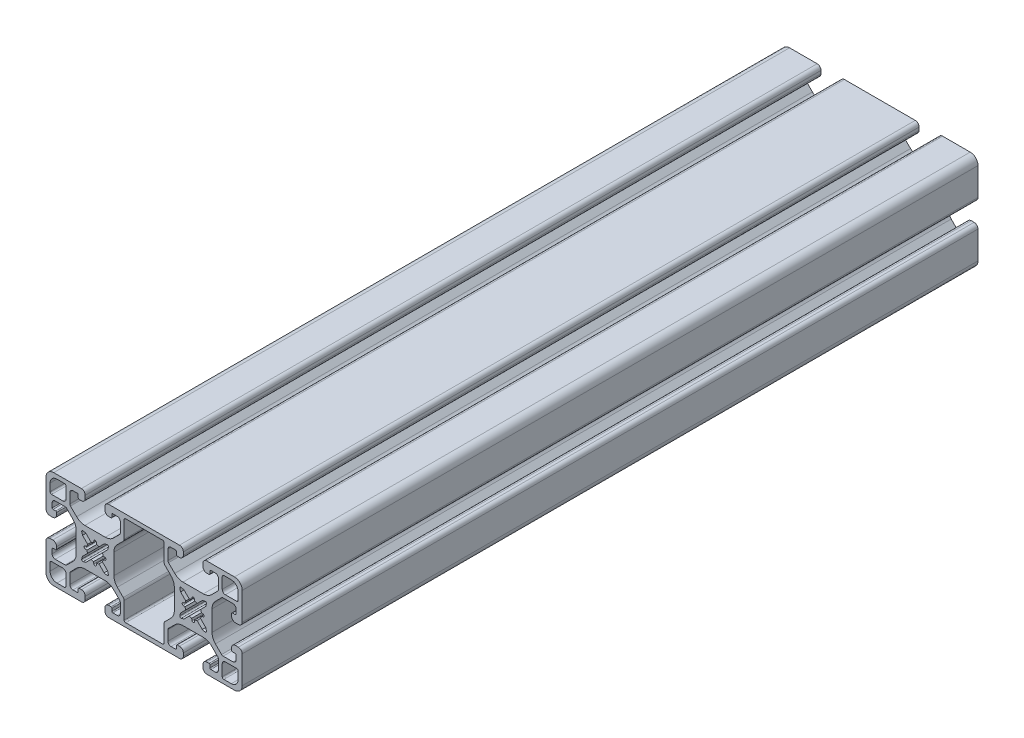
SolidWorks part; units mm, degrees
material "6105-T5 Aluminum"
ref_plane "Front Plane" through (0, 0, 0) normal (0, 0, 1) x (1, 0, 0)
ref_plane "Top Plane" through (0, 0, 0) normal (0, 1, 0) x (1, 0, 0)
ref_plane "Right Plane" through (0, 0, 0) normal (1, 0, 0) x (0, 0, -1)
sketch "Sketch1" plane through (0, 0, 0) normal (0, 0, 1) x (1, 0, 0)
  line L0 (-44, -18.4848) -> (-44, -17.255)
  line L1 (-46.474, -15.685) -> (-45.57, -15.685)
  line L2 (-56.83, -20) -> (-45.569, -20)
  line L3 (-46.855, -17.119) -> (-46.855, -16.066)
  line L4 (-60, -16.83) -> (-60, -5.57)
  line L5 (-49.015, -17.5) -> (-47.236, -17.5)
  line L6 (-58.43, -4) -> (-57.255, -4)
  line L7 (-50.285, -16.23) -> (-50.285, -12.2162)
  line L8 (-55.685, -5.57) -> (-55.685, -6.474)
  line L9 (-47.5137, -9.0762) -> (-50.0243, -11.5869)
  line L10 (-57.119, -6.855) -> (-56.066, -6.855)
  line L11 (-44.1549, -7.685) -> (-35.8451, -7.685)
  line L12 (-57.5, -9.015) -> (-57.5, -7.236)
  line L13 (-32.4863, -9.0762) -> (-29.9757, -11.5869)
  line L14 (-56.23, -10.285) -> (-52.2162, -10.285)
  line L15 (-29.715, -16.23) -> (-29.715, -12.2162)
  line L16 (-49.0762, -7.5137) -> (-51.5869, -10.0243)
  line L17 (-30.985, -17.5) -> (-32.764, -17.5)
  line L18 (-47.685, 4.1549) -> (-47.685, -4.1549)
  line L19 (-33.145, -17.119) -> (-33.145, -16.066)
  line L20 (-49.0762, 7.5137) -> (-51.5869, 10.0243)
  line L21 (-34.43, -15.685) -> (-33.526, -15.685)
  line L22 (-56.23, 10.285) -> (-52.2162, 10.285)
  line L23 (-36, -18.4848) -> (-36, -17.255)
  line L24 (-57.5, 9.015) -> (-57.5, 7.236)
  line L25 (-5.57, -20) -> (-34.431, -20)
  line L26 (-57.119, 6.855) -> (-56.066, 6.855)
  line L27 (-4, -17.255) -> (-4, -18.43)
  line L28 (-55.685, 6.474) -> (-55.685, 5.57)
  line L29 (-5.57, -15.685) -> (-6.474, -15.685)
  line L30 (-58.43, 4) -> (-57.255, 4)
  line L31 (-6.855, -17.119) -> (-6.855, -16.066)
  line L32 (-60, 16.83) -> (-60, 5.57)
  line L33 (-9.015, -17.5) -> (-7.236, -17.5)
  line L34 (-56.83, 20) -> (-45.57, 20)
  line L35 (-10.285, -16.23) -> (-10.285, -12.2162)
  line L36 (-44, 18.43) -> (-44, 17.255)
  line L37 (-7.5137, -9.0762) -> (-10.0243, -11.5869)
  line L38 (-45.57, 15.685) -> (-46.474, 15.685)
  line L39 (4.1549, -7.685) -> (-4.1549, -7.685)
  line L40 (-46.855, 17.119) -> (-46.855, 16.066)
  line L41 (7.5137, -9.0762) -> (10.0243, -11.5869)
  line L42 (-49.015, 17.5) -> (-47.236, 17.5)
  line L43 (10.285, -16.23) -> (10.285, -12.2162)
  line L44 (-50.285, 16.23) -> (-50.285, 12.2162)
  line L45 (9.015, -17.5) -> (7.236, -17.5)
  line L46 (-47.5137, 9.0762) -> (-50.0243, 11.5869)
  line L47 (6.855, -17.119) -> (6.855, -16.066)
  line L48 (-35.8451, 7.685) -> (-44.1549, 7.685)
  line L49 (6.474, -15.685) -> (5.57, -15.685)
  line L50 (-32.4863, 9.0762) -> (-29.9757, 11.5869)
  line L51 (4, -17.255) -> (4, -18.43)
  line L52 (-29.715, 16.23) -> (-29.715, 12.2162)
  line L53 (16.83, -20) -> (5.57, -20)
  line L54 (-30.985, 17.5) -> (-32.764, 17.5)
  line L55 (20, -16.83) -> (20, -5.57)
  line L56 (-33.145, 17.119) -> (-33.145, 16.066)
  line L57 (17.255, -4) -> (18.43, -4)
  line L58 (-33.526, 15.685) -> (-34.43, 15.685)
  line L59 (15.685, -5.57) -> (15.685, -6.474)
  line L60 (-36, 18.43) -> (-36, 17.255)
  line L61 (17.119, -6.855) -> (16.066, -6.855)
  line L62 (-34.43, 20) -> (-5.57, 20)
  line L63 (17.5, -9.015) -> (17.5, -7.236)
  line L64 (-4, 18.43) -> (-4, 17.255)
  line L65 (16.23, -10.285) -> (12.2162, -10.285)
  line L66 (-6.474, 15.685) -> (-5.57, 15.685)
  line L67 (9.0762, -7.5137) -> (11.5869, -10.0243)
  line L68 (-6.855, 17.119) -> (-6.855, 16.066)
  line L69 (7.685, 4.1549) -> (7.685, -4.1549)
  line L70 (-9.015, 17.5) -> (-7.236, 17.5)
  line L71 (9.0762, 7.5137) -> (11.5869, 10.0243)
  line L72 (-10.285, 16.23) -> (-10.285, 12.2162)
  line L73 (16.23, 10.285) -> (12.2162, 10.285)
  line L74 (-7.5137, 9.0762) -> (-10.0243, 11.5869)
  line L75 (17.5, 9.015) -> (17.5, 7.236)
  line L76 (-4.1549, 7.685) -> (4.1549, 7.685)
  line L77 (17.119, 6.855) -> (16.066, 6.855)
  line L78 (7.5137, 9.0762) -> (10.0243, 11.5869)
  line L79 (15.685, 6.474) -> (15.685, 5.57)
  line L80 (10.285, 16.23) -> (10.285, 12.2162)
  line L81 (17.255, 4) -> (18.43, 4)
  line L82 (9.015, 17.5) -> (7.236, 17.5)
  line L83 (20, 16.83) -> (20, 5.57)
  line L84 (6.855, 17.119) -> (6.855, 16.066)
  line L85 (16.83, 20) -> (5.57, 20)
  line L86 (5.57, 15.685) -> (6.474, 15.685)
  line L87 (4, 18.43) -> (4, 17.255)
  line L88 (15.545, -18.345) -> (12.4898, -18.345)
  line L89 (18.345, -12.4898) -> (18.345, -15.545)
  line L90 (11.8598, -17.715) -> (11.8598, -13.1298)
  line L91 (13.1298, -11.8598) -> (17.715, -11.8598)
  line L92 (-11.8598, 17.715) -> (-11.8598, 10.8233)
  line L93 (-11.4878, 9.9253) -> (-9.0762, 7.5137)
  line L94 (-27.5102, 18.345) -> (-12.4898, 18.345)
  line L95 (-7.685, 4.1549) -> (-7.685, -4.1549)
  line L96 (-28.1402, 10.8233) -> (-28.1402, 17.715)
  line L97 (-9.0762, -7.5137) -> (-11.4878, -9.9253)
  line L98 (-30.9238, 7.5137) -> (-28.5122, 9.9253)
  line L99 (-11.8598, -10.8233) -> (-11.8598, -17.715)
  line L100 (-32.315, -4.1549) -> (-32.315, 4.1549)
  line L101 (-12.4898, -18.345) -> (-27.5102, -18.345)
  line L102 (-28.5122, -9.9253) -> (-30.9238, -7.5137)
  line L103 (-28.1402, -17.715) -> (-28.1402, -10.8233)
  line L104 (-58.345, -15.545) -> (-58.345, -12.4898)
  line L105 (-52.4898, -18.345) -> (-55.545, -18.345)
  line L106 (-57.715, -11.8598) -> (-53.1298, -11.8598)
  line L107 (-51.8598, -13.1298) -> (-51.8598, -17.715)
  line L108 (-55.545, 18.345) -> (-52.4898, 18.345)
  line L109 (-58.345, 12.4898) -> (-58.345, 15.545)
  line L110 (-51.8598, 17.715) -> (-51.8598, 13.1298)
  line L111 (-53.1298, 11.8598) -> (-57.715, 11.8598)
  line L112 (18.345, 15.545) -> (18.345, 12.4898)
  line L113 (12.4898, 18.345) -> (15.545, 18.345)
  line L114 (17.715, 11.8598) -> (13.1298, 11.8598)
  line L115 (11.8598, 13.1298) -> (11.8598, 17.715)
  line L116 (-34.8737, -3.712) -> (-34.5607, -4.8481)
  line L117 (-36.9951, -1.5907) -> (-34.8737, -3.712)
  line L118 (-35.1519, -5.4393) -> (-36.288, -5.1263)
  line L119 (-36.288, -5.1263) -> (-38.4093, -3.0049)
  line L120 (-35.9124, -0.4923) -> (-36.6579, -0.625)
  line L121 (-39.375, -3.3421) -> (-39.5077, -4.0876)
  line L122 (-36.6579, 0.625) -> (-35.9124, 0.4923)
  line L123 (-40.4923, -4.0876) -> (-40.625, -3.3421)
  line L124 (-34.8737, 3.712) -> (-36.9951, 1.5907)
  line L125 (-34.5607, 4.8481) -> (-34.8737, 3.712)
  line L126 (-41.5907, -3.0049) -> (-43.712, -5.1263)
  line L127 (-43.712, -5.1263) -> (-44.8481, -5.4393)
  line L128 (-36.288, 5.1263) -> (-35.1519, 5.4393)
  line L129 (-38.4093, 3.0049) -> (-36.288, 5.1263)
  line L130 (-45.4393, -4.8481) -> (-45.1263, -3.712)
  line L131 (-45.1263, -3.712) -> (-43.0049, -1.5907)
  line L132 (-39.5077, 4.0876) -> (-39.375, 3.3421)
  line L133 (-43.3421, -0.625) -> (-44.0876, -0.4923)
  line L134 (-40.625, 3.3421) -> (-40.4923, 4.0876)
  line L135 (-44.0876, 0.4923) -> (-43.3421, 0.625)
  line L136 (-43.712, 5.1263) -> (-41.5907, 3.0049)
  line L137 (-44.8481, 5.4393) -> (-43.712, 5.1263)
  line L138 (-43.0049, 1.5907) -> (-45.1263, 3.712)
  line L139 (-45.1263, 3.712) -> (-45.4393, 4.8481)
  line L140 (5.1263, -3.712) -> (5.4393, -4.8481)
  line L141 (3.0049, -1.5907) -> (5.1263, -3.712)
  line L142 (4.8481, -5.4393) -> (3.712, -5.1263)
  line L143 (3.712, -5.1263) -> (1.5907, -3.0049)
  line L144 (4.0876, -0.4923) -> (3.3421, -0.625)
  line L145 (0.625, -3.3421) -> (0.4923, -4.0876)
  line L146 (3.3421, 0.625) -> (4.0876, 0.4923)
  line L147 (-0.4923, -4.0876) -> (-0.625, -3.3421)
  line L148 (5.1263, 3.712) -> (3.0049, 1.5907)
  line L149 (5.4393, 4.8481) -> (5.1263, 3.712)
  line L150 (-1.5907, -3.0049) -> (-3.712, -5.1263)
  line L151 (-3.712, -5.1263) -> (-4.8481, -5.4393)
  line L152 (3.712, 5.1263) -> (4.8481, 5.4393)
  line L153 (1.5907, 3.0049) -> (3.712, 5.1263)
  line L154 (-5.4393, -4.8481) -> (-5.1263, -3.712)
  line L155 (-5.1263, -3.712) -> (-3.0049, -1.5907)
  line L156 (0.4923, 4.0876) -> (0.625, 3.3421)
  line L157 (-3.3421, -0.625) -> (-4.0876, -0.4923)
  line L158 (-0.625, 3.3421) -> (-0.4923, 4.0876)
  line L159 (-4.0876, 0.4923) -> (-3.3421, 0.625)
  line L160 (-3.712, 5.1263) -> (-1.5907, 3.0049)
  line L161 (-4.8481, 5.4393) -> (-3.712, 5.1263)
  line L162 (-3.0049, 1.5907) -> (-5.1263, 3.712)
  line L163 (-5.1263, 3.712) -> (-5.4393, 4.8481)
  arc A0 (-44, -17.255) -> (-45.57, -15.685) centre (-45.57, -17.255) ccw
  arc A1 (-45.569, -20) -> (-44, -18.4848) centre (-45.569, -18.43) ccw
  arc A2 (-46.474, -15.685) -> (-46.855, -16.066) centre (-46.474, -16.066) ccw
  arc A3 (-60, -16.83) -> (-56.83, -20) centre (-56.83, -16.83) ccw
  arc A4 (-47.236, -17.5) -> (-46.855, -17.119) centre (-47.236, -17.119) ccw
  arc A5 (-58.43, -4) -> (-60, -5.57) centre (-58.43, -5.57) ccw
  arc A6 (-50.285, -16.23) -> (-49.015, -17.5) centre (-49.015, -16.23) ccw
  arc A7 (-55.685, -5.57) -> (-57.255, -4) centre (-57.255, -5.57) ccw
  arc A8 (-50.0243, -11.5869) -> (-50.285, -12.2162) centre (-49.395, -12.2162) ccw
  arc A9 (-56.066, -6.855) -> (-55.685, -6.474) centre (-56.066, -6.474) ccw
  arc A10 (-44.1549, -7.685) -> (-47.5137, -9.0762) centre (-44.1549, -12.435) ccw
  arc A11 (-57.119, -6.855) -> (-57.5, -7.236) centre (-57.119, -7.236) ccw
  arc A12 (-32.4863, -9.0762) -> (-35.8451, -7.685) centre (-35.8451, -12.435) ccw
  arc A13 (-57.5, -9.015) -> (-56.23, -10.285) centre (-56.23, -9.015) ccw
  arc A14 (-29.715, -12.2162) -> (-29.9757, -11.5869) centre (-30.605, -12.2162) ccw
  arc A15 (-52.2162, -10.285) -> (-51.5869, -10.0243) centre (-52.2162, -9.395) ccw
  arc A16 (-30.985, -17.5) -> (-29.715, -16.23) centre (-30.985, -16.23) ccw
  arc A17 (-49.0762, -7.5137) -> (-47.685, -4.1549) centre (-52.435, -4.1549) ccw
  arc A18 (-33.145, -17.119) -> (-32.764, -17.5) centre (-32.764, -17.119) ccw
  arc A19 (-47.685, 4.1549) -> (-49.0762, 7.5137) centre (-52.435, 4.1549) ccw
  arc A20 (-33.145, -16.066) -> (-33.526, -15.685) centre (-33.526, -16.066) ccw
  arc A21 (-51.5869, 10.0243) -> (-52.2162, 10.285) centre (-52.2162, 9.395) ccw
  arc A22 (-34.43, -15.685) -> (-36, -17.255) centre (-34.43, -17.255) ccw
  arc A23 (-56.23, 10.285) -> (-57.5, 9.015) centre (-56.23, 9.015) ccw
  arc A24 (-36, -18.4848) -> (-34.431, -20) centre (-34.431, -18.43) ccw
  arc A25 (-57.5, 7.236) -> (-57.119, 6.855) centre (-57.119, 7.236) ccw
  arc A26 (-5.57, -20) -> (-4, -18.43) centre (-5.57, -18.43) ccw
  arc A27 (-55.685, 6.474) -> (-56.066, 6.855) centre (-56.066, 6.474) ccw
  arc A28 (-4, -17.255) -> (-5.57, -15.685) centre (-5.57, -17.255) ccw
  arc A29 (-57.255, 4) -> (-55.685, 5.57) centre (-57.255, 5.57) ccw
  arc A30 (-6.474, -15.685) -> (-6.855, -16.066) centre (-6.474, -16.066) ccw
  arc A31 (-60, 5.57) -> (-58.43, 4) centre (-58.43, 5.57) ccw
  arc A32 (-7.236, -17.5) -> (-6.855, -17.119) centre (-7.236, -17.119) ccw
  arc A33 (-56.83, 20) -> (-60, 16.83) centre (-56.83, 16.83) ccw
  arc A34 (-10.285, -16.23) -> (-9.015, -17.5) centre (-9.015, -16.23) ccw
  arc A35 (-44, 18.43) -> (-45.57, 20) centre (-45.57, 18.43) ccw
  arc A36 (-10.0243, -11.5869) -> (-10.285, -12.2162) centre (-9.395, -12.2162) ccw
  arc A37 (-45.57, 15.685) -> (-44, 17.255) centre (-45.57, 17.255) ccw
  arc A38 (-4.1549, -7.685) -> (-7.5137, -9.0762) centre (-4.1549, -12.435) ccw
  arc A39 (-46.855, 16.066) -> (-46.474, 15.685) centre (-46.474, 16.066) ccw
  arc A40 (7.5137, -9.0762) -> (4.1549, -7.685) centre (4.1549, -12.435) ccw
  arc A41 (-46.855, 17.119) -> (-47.236, 17.5) centre (-47.236, 17.119) ccw
  arc A42 (10.285, -12.2162) -> (10.0243, -11.5869) centre (9.395, -12.2162) ccw
  arc A43 (-49.015, 17.5) -> (-50.285, 16.23) centre (-49.015, 16.23) ccw
  arc A44 (9.015, -17.5) -> (10.285, -16.23) centre (9.015, -16.23) ccw
  arc A45 (-50.285, 12.2162) -> (-50.0243, 11.5869) centre (-49.395, 12.2162) ccw
  arc A46 (6.855, -17.119) -> (7.236, -17.5) centre (7.236, -17.119) ccw
  arc A47 (-47.5137, 9.0762) -> (-44.1549, 7.685) centre (-44.1549, 12.435) ccw
  arc A48 (6.855, -16.066) -> (6.474, -15.685) centre (6.474, -16.066) ccw
  arc A49 (-35.8451, 7.685) -> (-32.4863, 9.0762) centre (-35.8451, 12.435) ccw
  arc A50 (5.57, -15.685) -> (4, -17.255) centre (5.57, -17.255) ccw
  arc A51 (-29.9757, 11.5869) -> (-29.715, 12.2162) centre (-30.605, 12.2162) ccw
  arc A52 (4, -18.43) -> (5.57, -20) centre (5.57, -18.43) ccw
  arc A53 (-29.715, 16.23) -> (-30.985, 17.5) centre (-30.985, 16.23) ccw
  arc A54 (16.83, -20) -> (20, -16.83) centre (16.83, -16.83) ccw
  arc A55 (-32.764, 17.5) -> (-33.145, 17.119) centre (-32.764, 17.119) ccw
  arc A56 (20, -5.57) -> (18.43, -4) centre (18.43, -5.57) ccw
  arc A57 (-33.526, 15.685) -> (-33.145, 16.066) centre (-33.526, 16.066) ccw
  arc A58 (17.255, -4) -> (15.685, -5.57) centre (17.255, -5.57) ccw
  arc A59 (-36, 17.255) -> (-34.43, 15.685) centre (-34.43, 17.255) ccw
  arc A60 (15.685, -6.474) -> (16.066, -6.855) centre (16.066, -6.474) ccw
  arc A61 (-34.43, 20) -> (-36, 18.43) centre (-34.43, 18.43) ccw
  arc A62 (17.5, -7.236) -> (17.119, -6.855) centre (17.119, -7.236) ccw
  arc A63 (-4, 18.43) -> (-5.57, 20) centre (-5.57, 18.43) ccw
  arc A64 (16.23, -10.285) -> (17.5, -9.015) centre (16.23, -9.015) ccw
  arc A65 (-5.57, 15.685) -> (-4, 17.255) centre (-5.57, 17.255) ccw
  arc A66 (11.5869, -10.0243) -> (12.2162, -10.285) centre (12.2162, -9.395) ccw
  arc A67 (-6.855, 16.066) -> (-6.474, 15.685) centre (-6.474, 16.066) ccw
  arc A68 (7.685, -4.1549) -> (9.0762, -7.5137) centre (12.435, -4.1549) ccw
  arc A69 (-6.855, 17.119) -> (-7.236, 17.5) centre (-7.236, 17.119) ccw
  arc A70 (9.0762, 7.5137) -> (7.685, 4.1549) centre (12.435, 4.1549) ccw
  arc A71 (-9.015, 17.5) -> (-10.285, 16.23) centre (-9.015, 16.23) ccw
  arc A72 (12.2162, 10.285) -> (11.5869, 10.0243) centre (12.2162, 9.395) ccw
  arc A73 (-10.285, 12.2162) -> (-10.0243, 11.5869) centre (-9.395, 12.2162) ccw
  arc A74 (17.5, 9.015) -> (16.23, 10.285) centre (16.23, 9.015) ccw
  arc A75 (-7.5137, 9.0762) -> (-4.1549, 7.685) centre (-4.1549, 12.435) ccw
  arc A76 (17.119, 6.855) -> (17.5, 7.236) centre (17.119, 7.236) ccw
  arc A77 (4.1549, 7.685) -> (7.5137, 9.0762) centre (4.1549, 12.435) ccw
  arc A78 (16.066, 6.855) -> (15.685, 6.474) centre (16.066, 6.474) ccw
  arc A79 (10.0243, 11.5869) -> (10.285, 12.2162) centre (9.395, 12.2162) ccw
  arc A80 (15.685, 5.57) -> (17.255, 4) centre (17.255, 5.57) ccw
  arc A81 (10.285, 16.23) -> (9.015, 17.5) centre (9.015, 16.23) ccw
  arc A82 (18.43, 4) -> (20, 5.57) centre (18.43, 5.57) ccw
  arc A83 (7.236, 17.5) -> (6.855, 17.119) centre (7.236, 17.119) ccw
  arc A84 (20, 16.83) -> (16.83, 20) centre (16.83, 16.83) ccw
  arc A85 (6.474, 15.685) -> (6.855, 16.066) centre (6.474, 16.066) ccw
  arc A86 (5.57, 20) -> (4, 18.43) centre (5.57, 18.43) ccw
  arc A87 (4, 17.255) -> (5.57, 15.685) centre (5.57, 17.255) ccw
  arc A88 (15.545, -18.345) -> (18.345, -15.545) centre (15.545, -15.545) ccw
  arc A89 (11.8598, -17.715) -> (12.4898, -18.345) centre (12.4898, -17.715) ccw
  arc A90 (18.345, -12.4898) -> (17.715, -11.8598) centre (17.715, -12.4898) ccw
  arc A91 (13.1298, -11.8598) -> (11.8598, -13.1298) centre (13.1298, -13.1298) ccw
  arc A92 (-11.8598, 10.8233) -> (-11.4878, 9.9253) centre (-10.5898, 10.8233) ccw
  arc A93 (-11.8598, 17.715) -> (-12.4898, 18.345) centre (-12.4898, 17.715) ccw
  arc A94 (-7.685, 4.1549) -> (-9.0762, 7.5137) centre (-12.435, 4.1549) ccw
  arc A95 (-27.5102, 18.345) -> (-28.1402, 17.715) centre (-27.5102, 17.715) ccw
  arc A96 (-9.0762, -7.5137) -> (-7.685, -4.1549) centre (-12.435, -4.1549) ccw
  arc A97 (-28.5122, 9.9253) -> (-28.1402, 10.8233) centre (-29.4102, 10.8233) ccw
  arc A98 (-11.4878, -9.9253) -> (-11.8598, -10.8233) centre (-10.5898, -10.8233) ccw
  arc A99 (-30.9238, 7.5137) -> (-32.315, 4.1549) centre (-27.565, 4.1549) ccw
  arc A100 (-12.4898, -18.345) -> (-11.8598, -17.715) centre (-12.4898, -17.715) ccw
  arc A101 (-32.315, -4.1549) -> (-30.9238, -7.5137) centre (-27.565, -4.1549) ccw
  arc A102 (-28.1402, -17.715) -> (-27.5102, -18.345) centre (-27.5102, -17.715) ccw
  arc A103 (-28.1402, -10.8233) -> (-28.5122, -9.9253) centre (-29.4102, -10.8233) ccw
  arc A104 (-58.345, -15.545) -> (-55.545, -18.345) centre (-55.545, -15.545) ccw
  arc A105 (-57.715, -11.8598) -> (-58.345, -12.4898) centre (-57.715, -12.4898) ccw
  arc A106 (-52.4898, -18.345) -> (-51.8598, -17.715) centre (-52.4898, -17.715) ccw
  arc A107 (-51.8598, -13.1298) -> (-53.1298, -11.8598) centre (-53.1298, -13.1298) ccw
  arc A108 (-55.545, 18.345) -> (-58.345, 15.545) centre (-55.545, 15.545) ccw
  arc A109 (-51.8598, 17.715) -> (-52.4898, 18.345) centre (-52.4898, 17.715) ccw
  arc A110 (-58.345, 12.4898) -> (-57.715, 11.8598) centre (-57.715, 12.4898) ccw
  arc A111 (-53.1298, 11.8598) -> (-51.8598, 13.1298) centre (-53.1298, 13.1298) ccw
  arc A112 (18.345, 15.545) -> (15.545, 18.345) centre (15.545, 15.545) ccw
  arc A113 (17.715, 11.8598) -> (18.345, 12.4898) centre (17.715, 12.4898) ccw
  arc A114 (12.4898, 18.345) -> (11.8598, 17.715) centre (12.4898, 17.715) ccw
  arc A115 (11.8598, 13.1298) -> (13.1298, 11.8598) centre (13.1298, 13.1298) ccw
  arc A116 (-35.1519, -5.4393) -> (-34.5607, -4.8481) centre (-35.0503, -4.9497) ccw
  arc A117 (-36.9951, -1.5907) -> (-36.6579, -0.625) centre (-40, 0) ccw
  arc A118 (-39.375, -3.3421) -> (-38.4093, -3.0049) centre (-40, 0) ccw
  arc A119 (-35.9124, -0.4923) -> (-35.9124, 0.4923) centre (-36, 0) ccw
  arc A120 (-40.4923, -4.0876) -> (-39.5077, -4.0876) centre (-40, -4) ccw
  arc A121 (-36.6579, 0.625) -> (-36.9951, 1.5907) centre (-40, 0) ccw
  arc A122 (-41.5907, -3.0049) -> (-40.625, -3.3421) centre (-40, 0) ccw
  arc A123 (-34.5607, 4.8481) -> (-35.1519, 5.4393) centre (-35.0503, 4.9497) ccw
  arc A124 (-45.4393, -4.8481) -> (-44.8481, -5.4393) centre (-44.9497, -4.9497) ccw
  arc A125 (-38.4093, 3.0049) -> (-39.375, 3.3421) centre (-40, 0) ccw
  arc A126 (-43.3421, -0.625) -> (-43.0049, -1.5907) centre (-40, 0) ccw
  arc A127 (-39.5077, 4.0876) -> (-40.4923, 4.0876) centre (-40, 4) ccw
  arc A128 (-44.0876, 0.4923) -> (-44.0876, -0.4923) centre (-44, 0) ccw
  arc A129 (-40.625, 3.3421) -> (-41.5907, 3.0049) centre (-40, 0) ccw
  arc A130 (-43.0049, 1.5907) -> (-43.3421, 0.625) centre (-40, 0) ccw
  arc A131 (-44.8481, 5.4393) -> (-45.4393, 4.8481) centre (-44.9497, 4.9497) ccw
  arc A132 (4.8481, -5.4393) -> (5.4393, -4.8481) centre (4.9497, -4.9497) ccw
  arc A133 (3.0049, -1.5907) -> (3.3421, -0.625) centre (0, 0) ccw
  arc A134 (0.625, -3.3421) -> (1.5907, -3.0049) centre (0, 0) ccw
  arc A135 (4.0876, -0.4923) -> (4.0876, 0.4923) centre (4, 0) ccw
  arc A136 (-0.4923, -4.0876) -> (0.4923, -4.0876) centre (0, -4) ccw
  arc A137 (3.3421, 0.625) -> (3.0049, 1.5907) centre (0, 0) ccw
  arc A138 (-1.5907, -3.0049) -> (-0.625, -3.3421) centre (0, 0) ccw
  arc A139 (5.4393, 4.8481) -> (4.8481, 5.4393) centre (4.9497, 4.9497) ccw
  arc A140 (-5.4393, -4.8481) -> (-4.8481, -5.4393) centre (-4.9497, -4.9497) ccw
  arc A141 (1.5907, 3.0049) -> (0.625, 3.3421) centre (0, 0) ccw
  arc A142 (-3.3421, -0.625) -> (-3.0049, -1.5907) centre (0, 0) ccw
  arc A143 (0.4923, 4.0876) -> (-0.4923, 4.0876) centre (0, 4) ccw
  arc A144 (-4.0876, 0.4923) -> (-4.0876, -0.4923) centre (-4, 0) ccw
  arc A145 (-0.625, 3.3421) -> (-1.5907, 3.0049) centre (0, 0) ccw
  arc A146 (-3.0049, 1.5907) -> (-3.3421, 0.625) centre (0, 0) ccw
  arc A147 (-4.8481, 5.4393) -> (-5.4393, 4.8481) centre (-4.9497, 4.9497) ccw
extrude "Extrude1" add sketch "Sketch1" against normal blind 300
